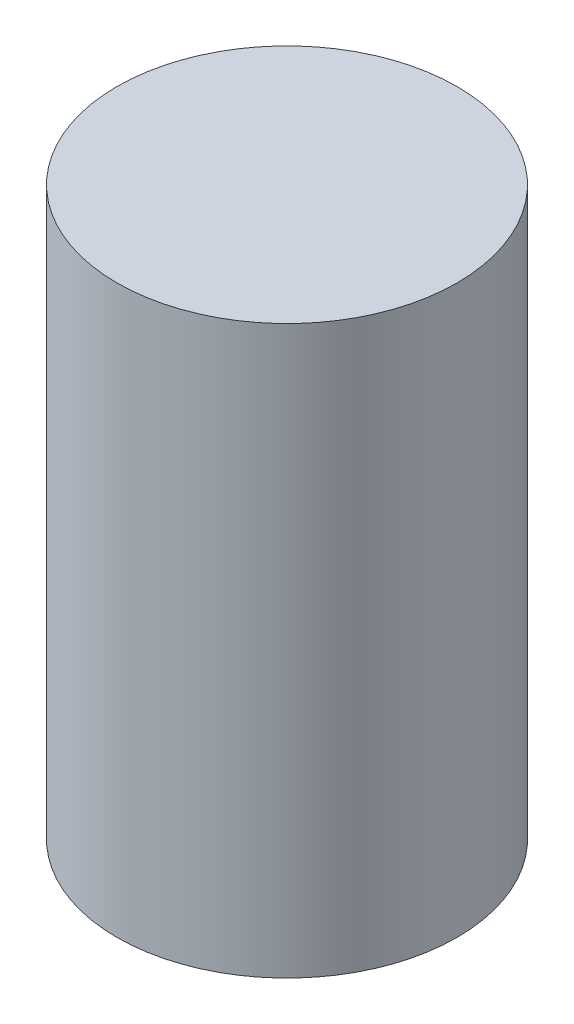
SolidWorks part; units mm, degrees
ref_plane "Front Plane" through (0, 0, 0) normal (0, 0, 1) x (1, 0, 0)
ref_plane "Top Plane" through (0, 0, 0) normal (0, 1, 0) x (1, 0, 0)
ref_plane "Right Plane" through (0, 0, 0) normal (1, 0, 0) x (0, 0, -1)
sketch "Sketch1" plane through (0, 0, 0) normal (0, 1, 0) x (1, 0, 0)
  circle A0 centre (0, 0) radius 30
  dimension "D1" = 60
extrude "Boss-Extrude1" add sketch "Sketch1" along normal blind 100
sketch "Sketch2" plane through (0, 0, 0) normal (0, -1, 0) x (1, 0, 0)
  circle A0 centre (0, 0) radius 10
  circle A1 centre (0, 22) radius 5
  circle A2 centre (0, -22) radius 5
  dimension "D2" = 10
  dimension "D3" = 20
  dimension "D4" = 10
  dimension "D1" = 22
  dimension "D5" = 22
extrude "Cut-Extrude1" cut sketch "Sketch2" against normal blind 20
